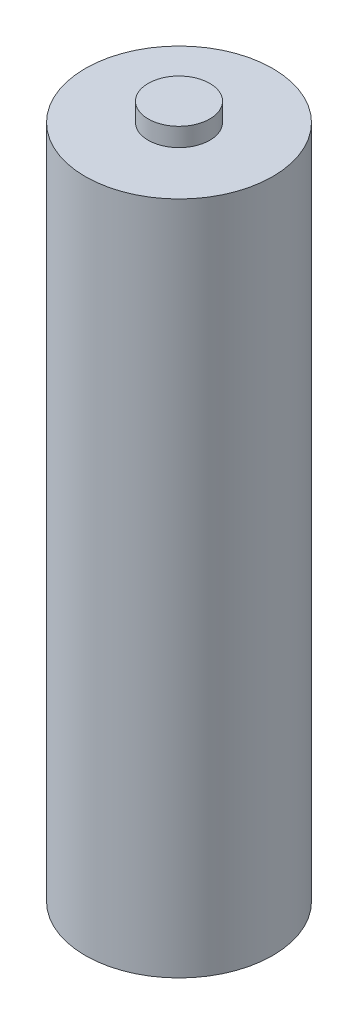
SolidWorks part; units mm, degrees
ref_plane "前视基准面" through (0, 0, 0) normal (0, 0, 1) x (1, 0, 0)
ref_plane "上视基准面" through (0, 0, 0) normal (0, 1, 0) x (1, 0, 0)
ref_plane "右视基准面" through (0, 0, 0) normal (1, 0, 0) x (0, 0, -1)
other "Configuration Table"
sketch "草图1" plane through (0, 0, 0) normal (0, 1, 0) x (1, 0, 0)
  circle A0 centre (0, 0) radius 9.125
  dimension "D1" = 18.25
extrude "凸台-拉伸1" add sketch "草图1" along normal blind 65.7
sketch "草图2" plane through (0, 65.7, 0) normal (0, 1, 0) x (1, 0, 0)
  circle A0 centre (0, 0) radius 3
  dimension "D1" = 6
extrude "凸台-拉伸2" add sketch "草图2" along normal blind 67.5 from surface at -65.7 starting at face at (0, 0, 9.125)
